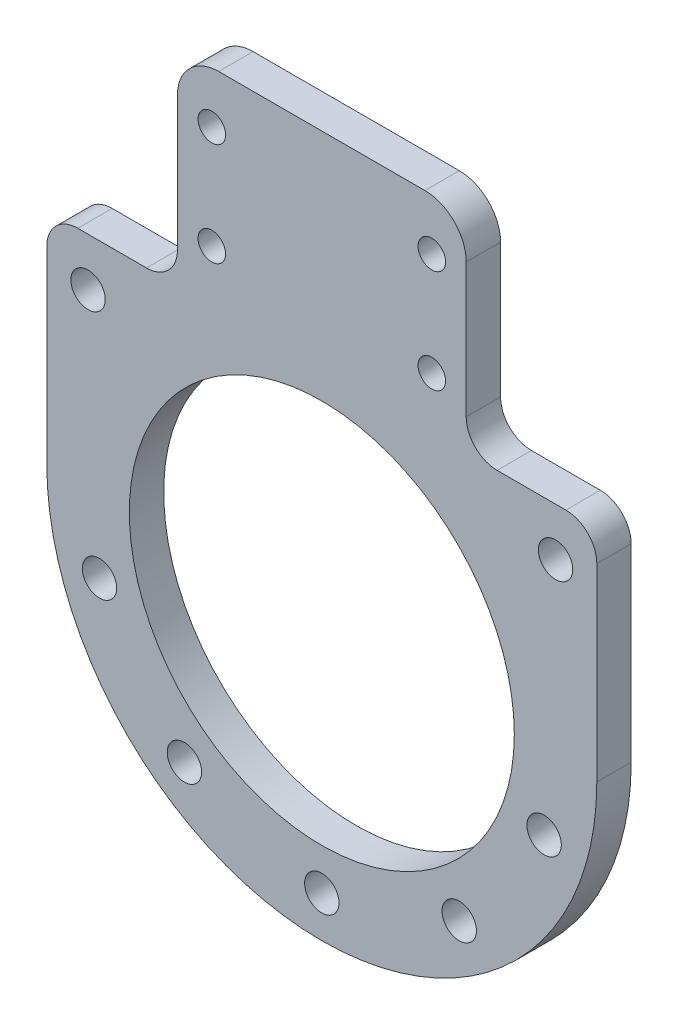
SolidWorks part; units mm, degrees
ref_plane "前视基准面" through (0, 0, 0) normal (0, 0, 1) x (1, 0, 0)
ref_plane "上视基准面" through (0, 0, 0) normal (0, 1, 0) x (1, 0, 0)
ref_plane "右视基准面" through (0, 0, 0) normal (1, 0, 0) x (0, 0, -1)
sketch "草图1" plane through (0, 0, 0) normal (0, 0, 1) x (1, 0, 0)
  line L0 (-26, 29.1235) -> (54, 29.1235)
  line L1 (54, 29.1235) -> (54, -32.8765)
  line L3 (-26, -32.8765) -> (-26, 29.1235)
  arc A0 (-26, -32.8765) -> (54, -32.8765) centre (14, -32.8765) ccw
  point P0 (0, 0)
  dimension "D1" = 80
  dimension "D2" = 62
extrude "凸台-拉伸1" add sketch "草图1" along normal blind 5
sketch "草图2" plane through (0, 0, 5) normal (0, 0, 1) x (1, 0, 0)
  circle A1 centre (14, -32.8765) radius 28
  dimension "D1" = 56
extrude "切除-拉伸1" cut sketch "草图2" against normal through all
sketch "草图3" plane through (0, 0, 5) normal (0, 0, 1) x (1, 0, 0)
  line L0 (54, 29.1235) -> (54, -0.8765)
  line L2 (54, -32.8765) -> (54, 29.1235) construction
  line L3 (54, -0.8765) -> (35, -0.8765)
  line L5 (35, -0.8765) -> (35, 29.1235)
  line L6 (54, 29.1235) -> (-26, 29.1235) construction
  line L7 (35, 29.1235) -> (54, 29.1235)
  dimension "D1" = 30
  dimension "D2" = 19
extrude "切除-拉伸2" cut sketch "草图3" against normal through all
fillet "圆角2" radius 4.5 2 edges at (54, -0.8765, 2.5) (35, -0.8765, 2.5)
sketch "草图4" plane through (0, 0, 5) normal (0, 0, 1) x (1, 0, 0)
  line L0 (-26, 29.1235) -> (-7, 29.1235)
  line L1 (35, 29.1235) -> (-26, 29.1235) construction
  line L2 (-7, 29.1235) -> (-7, -0.8765)
  line L3 (-7, -0.8765) -> (-26, -0.8765)
  line L4 (-26, 29.1235) -> (-26, -32.8765) construction
  line L5 (-26, -0.8765) -> (-26, 29.1235)
  dimension "D1" = 19
  dimension "D2" = 30
extrude "切除-拉伸3" cut sketch "草图4" against normal blind 5
fillet "圆角3" radius 4.5 2 edges at (-26, -0.8765, 2.5) (-7, -0.8765, 2.5)
sketch "草图6" plane through (0, 0, 5) normal (0, 0, 1) x (1, 0, 0)
  line L0 (-26, -5.3765) -> (-26, -32.8765) construction
  line L1 (54, -32.8765) -> (54, -5.3765) construction
  circle A0 centre (-20, -7.8765) radius 2.5
  circle A1 centre (48, -7.8765) radius 2.5
  circle A2 centre (14, -32.8765) radius 28 construction
  dimension "D1" = 25
  dimension "D2" = 25
  dimension "D3" = 6
  dimension "D4" = 6
  dimension "D5" = 5
  dimension "D6" = 5
extrude "切除-拉伸5" cut sketch "草图6" against normal through all
fillet "圆角4" radius 6 2 edges at (-7, 29.1235, 2.5) (35, 29.1235, 2.5)
sketch "草图7" plane through (0, 0, 5) normal (0, 0, 1) x (1, 0, 0)
  circle A0 centre (14, -66.8765) radius 2.5
  circle A2 centre (14, -32.8765) radius 28 construction
  circle A3 centre (-5.9847, -60.3831) radius 2.5
  circle A4 centre (-18.3359, -43.3831) radius 2.5
  circle A10 centre (46.3359, -43.3831) radius 2.5
  circle A18 centre (33.9847, -60.3831) radius 2.5
  circle A19 centre (14, 1.1235) radius 2.5 [skipped]
  circle A20 centre (-5.9847, -5.37) radius 2.5 [skipped]
  circle A21 centre (-18.3359, -22.37) radius 2.5 [skipped]
  circle A22 centre (33.9847, -5.37) radius 2.5 [skipped]
  circle A23 centre (46.3359, -22.37) radius 2.5 [skipped]
  point P24 (5.1279, -32.0568)
  point P40 (14, -32.8765)
  dimension "D1" = 34
  dimension "D2" = 5
  dimension "D3" = 10
extrude "切除-拉伸6" cut sketch "草图7" against normal through all
sketch "草图8" plane through (0, 0, 5) normal (0, 0, 1) x (1, 0, 0)
  line L0 (-7, 3.6235) -> (-7, 23.1235) construction
  line L1 (35, 23.1235) -> (35, 3.6235) construction
  line L2 (29, 29.1235) -> (-1, 29.1235) construction
  circle A0 centre (-2, 6.6235) radius 2
  circle A1 centre (-2, 21.6235) radius 2
  circle A2 centre (30, 21.6235) radius 2
  circle A3 centre (30, 6.6235) radius 2
  dimension "D1" = 5
  dimension "D2" = 5
  dimension "D3" = 5
  dimension "D4" = 5
  dimension "D5" = 15
  dimension "D6" = 15
  dimension "D7" = 4
  dimension "D8" = 4
  dimension "D9" = 4
  dimension "D10" = 4
  dimension "D11" = 7.5
  dimension "D12" = 7.5
extrude "切除-拉伸7" cut sketch "草图8" against normal through all
